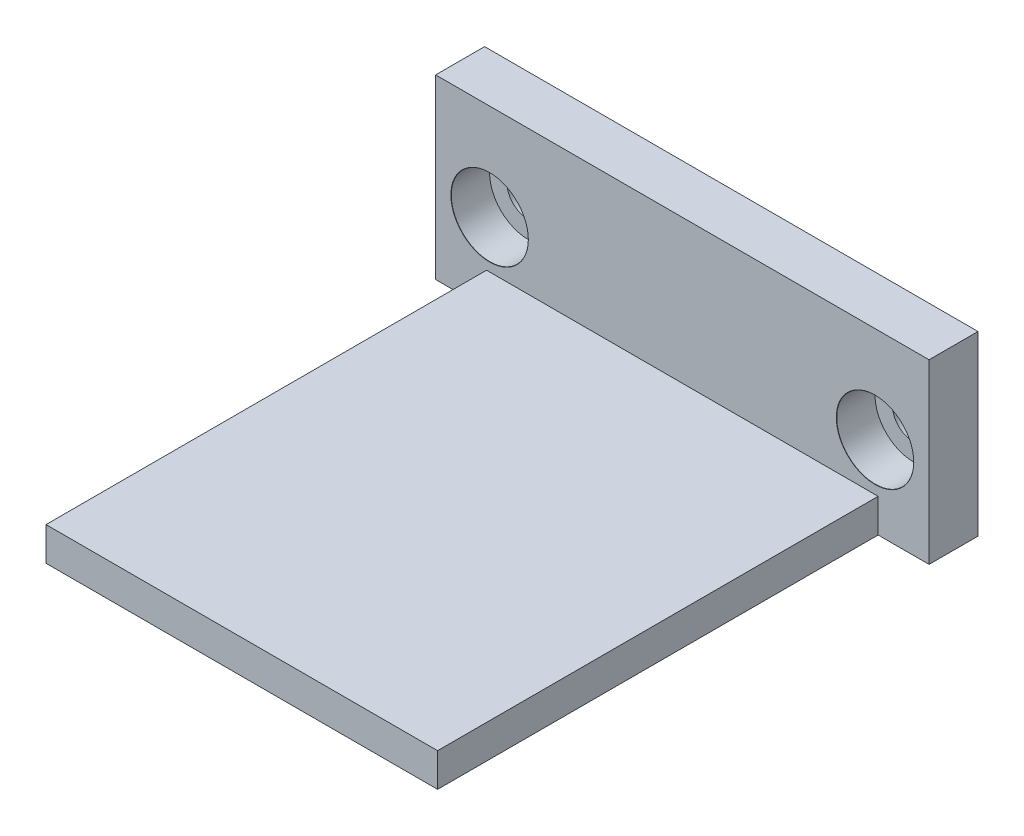
SolidWorks part; units mm, degrees
ref_plane "Front" through (0, 0, 0) normal (0, 0, 1) x (1, 0, 0)
ref_plane "Top" through (0, 0, 0) normal (0, 1, 0) x (1, 0, 0)
ref_plane "Right" through (0, 0, 0) normal (1, 0, 0) x (0, 0, -1)
sketch "Sketch1" plane through (0, 0, 0) normal (0, 0, 1) x (1, 0, 0)
  line L1 (0, 0) -> (64.008, 0)
  line L2 (0, 0) -> (0, 24.9936)
  line L3 (0, 24.9936) -> (64.008, 24.9936)
  line L4 (64.008, 0) -> (64.008, 24.9936)
  dimension "D1" = 24.9936
  dimension "D2" = 64.008
extrude "Boss-Extrude1" add sketch "Sketch1" along normal blind 6.35
sketch "Sketch2" plane through (0, 0, 6.35) normal (0, 0, 1) x (1, 0, 0)
  line L0 (64.008, 0) -> (64.008, 24.9936) construction
  line L1 (0, 0) -> (64.008, 0)
  line L2 (0, 0) -> (0, 6.35)
  line L3 (0, 6.35) -> (64.008, 6.35)
  line L4 (64.008, 0) -> (64.008, 6.35)
  dimension "D1" = 6.35
extrude "Boss-Extrude2" add sketch "Sketch2" along normal blind 57.15
sketch "Sketch5" plane through (0, 0, 6.35) normal (0, 0, 1) x (1, 0, 0)
  line L0 (-2.4403, 12.5) -> (65.3922, 12.5) construction
  line L1 (0, 0) -> (64.008, 0) construction
  line L2 (7, 27.9859) -> (7, -6.3192) construction
  line L3 (57, 30.103) -> (57, -4.1589) construction
  line L4 (0, 24.9936) -> (0, 6.35) construction
  dimension "D1" = 12.5
  dimension "D2" = 50
  dimension "D3" = 7
hole_wizard "CBORE for M5 SHCS1" positions "Sketch6" profile "Sketch7" counterbore size "M5" standard "ANSI Metric" end condition up to next
sketch "Sketch6" plane through (0, 0, 6.35) normal (0, 0, 1) x (1, 0, 0)
  line L0 (-2.4403, 12.5) -> (65.3922, 12.5) construction
  line L1 (7, 27.9859) -> (7, -6.3192) construction
  line L2 (57, 30.103) -> (57, -4.1589) construction
  point P0 (7, 12.5)
  point P6 (57, 12.5)
sketch "Sketch7" plane through (7, 12.5, 6.35) normal (1, 0, 0) x (0, -1, 0)
  line L0 (0, 0) -> (0, 6.35)
  line L1 (0, 6.35) -> (2.75, 6.35)
  line L3 (2.75, 6.35) -> (2.75, 5)
  line L4 (5, 5) -> (2.75, 5)
  line L5 (5, 5) -> (5, 0.025)
  line L6 (5, 0.025) -> (5.025, 0)
  line L7 (5.025, 0) -> (0, 0)
  line L8 (-5, 0.025) -> (-5.025, 0) construction
  line L11 (0, -6.35) -> (0, 107.95) construction
  dimension "Thru Hole Dia." = 5.5
  dimension "Thru Hole Depth" = 6.35
  dimension "C'Bore Dia." = 10
  dimension "C'Bore Depth" = 5
  dimension "Near C'Sink Dia." = 10.05
  dimension "Near C'Sink Angle" = 90
sketch "Sketch8" plane through (0, 0, 63.5) normal (0, 0, 1) x (1, 0, 0)
  line L0 (0, 0) -> (64.008, 0) construction
  line L1 (0, 6.35) -> (6.604, 6.35)
  line L2 (0, 6.35) -> (0, 0)
  line L3 (0, 0) -> (6.604, 0)
  line L4 (6.604, 6.35) -> (6.604, 0)
  line L6 (64.008, 6.35) -> (57.404, 6.35)
  line L7 (64.008, 6.35) -> (64.008, 0)
  line L8 (64.008, 0) -> (57.404, 0)
  line L9 (57.404, 6.35) -> (57.404, 0)
  dimension "D1" = 6.604
  dimension "D2" = 6.604
extrude "Cut-Extrude1" cut sketch "Sketch8" against normal up to surface (57.15 mm away) up to face at (32.004, 15.6718, 6.35)
sketch "Sketch9" plane through (0, 0, 6.35) normal (0, 0, 1) x (1, 0, 0)
  line L0 (64.008, 0) -> (64.008, 24.9936) construction
  line L1 (0, 0) -> (64.008, 0)
  line L2 (0, 0) -> (0, 2)
  line L3 (0, 2) -> (64.008, 2)
  line L4 (64.008, 0) -> (64.008, 2)
  dimension "D1" = 2
extrude "Cut-Extrude2" cut sketch "Sketch9" against normal through all both and the other way through all
